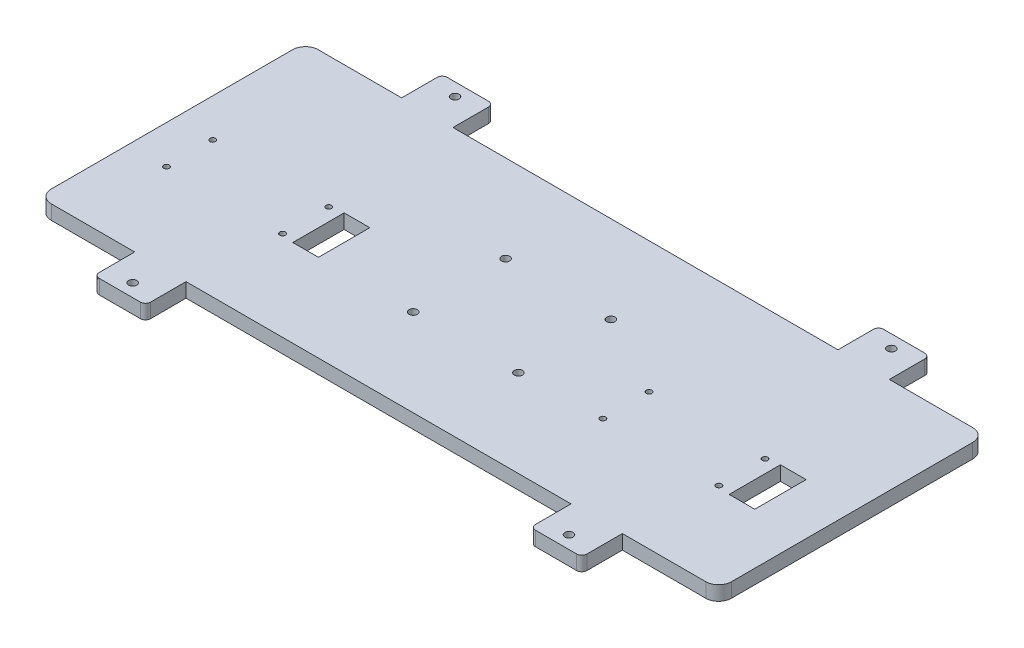
SolidWorks part; units mm, degrees
material "t5ハニカムプラダン"
ref_plane "正面" through (0, 0, 0) normal (0, 0, 1) x (1, 0, 0)
ref_plane "平面" through (0, 0, 0) normal (0, 1, 0) x (1, 0, 0)
ref_plane "右側面" through (0, 0, 0) normal (1, 0, 0) x (0, 0, -1)
sketch "ｽｹｯﾁ1" plane through (0, 0, 0) normal (0, 1, 0) x (1, 0, 0)
  line L1 (-132.5, 52) -> (132.5, 52)
  line L2 (-132.5, 52) -> (-132.5, -52)
  line L3 (-132.5, -52) -> (132.5, -52)
  line L4 (132.5, 52) -> (132.5, -52)
  line L5 (-132.5, 52) -> (132.5, -52) construction
  line L6 (-132.5, -52) -> (132.5, 52) construction
  point P0 (0, 0)
  dimension "D1" = 265
  dimension "D2" = 104
extrude "ﾎﾞｽ - 押し出し1" add sketch "ｽｹｯﾁ1" along normal blind 5.6
sketch "ｽｹｯﾁ2" plane through (0, 0, 0) normal (0, 1, 0) x (1, 0, 0)
  line L0 (0, 52) -> (0, 0) construction
  line L1 (132.5, 52) -> (-132.5, 52) construction
  line L2 (0, 0) -> (20.5, 0) construction
  line L3 (-20.5, 18) -> (20.5, 18) construction
  line L4 (-20.5, 18) -> (-20.5, -18) construction
  line L5 (-20.5, -18) -> (20.5, -18) construction
  line L6 (20.5, 18) -> (20.5, -18) construction
  line L7 (-20.5, 18) -> (20.5, -18) construction
  line L8 (-20.5, -18) -> (20.5, 18) construction
  circle A0 centre (20.5, 18) radius 1.6
  circle A1 centre (20.5, -18) radius 1.6
  circle A2 centre (-20.5, -18) radius 1.6
  circle A3 centre (-20.5, 18) radius 1.6
  dimension "D4" = 3.2
  dimension "D1" = 41
  dimension "D2" = 36
  dimension "D3" = 52
extrude "ｶｯﾄ - 押し出し4" cut sketch "ｽｹｯﾁ2" along normal through all
sketch "ｽｹｯﾁ4" plane through (0, 5.6, 0) normal (0, 1, 0) x (1, 0, 0)
  line L0 (0, 0) -> (0, 52) construction
  line L1 (132.5, 52) -> (-132.5, 52) construction
  line L2 (75, 1) -> (75, -8) construction
  line L3 (52.4, 1) -> (97.6, 1) construction
  line L4 (52.4, 1) -> (52.4, -17) construction
  line L5 (52.4, -17) -> (97.6, -17) construction
  line L6 (97.6, 1) -> (97.6, -17) construction
  line L7 (52.4, 1) -> (97.6, -17) construction
  line L8 (52.4, -17) -> (97.6, 1) construction
  line L9 (75, -8) -> (97.6, -8) construction
  line L10 (97.6, -8) -> (107.6, -8) construction
  line L11 (-67.4, 2) -> (-57.4, 2)
  line L16 (102.6, 2) -> (112.6, 2)
  line L17 (102.6, 2) -> (102.6, -18)
  line L18 (102.6, -18) -> (112.6, -18)
  line L19 (112.6, 2) -> (112.6, -18)
  line L20 (-67.4, 2) -> (-67.4, -18)
  line L21 (-67.4, -18) -> (-57.4, -18)
  line L22 (-57.4, 2) -> (-57.4, -18)
  line L23 (-95, 1) -> (-95, -8) construction
  line L24 (-117.6, 1) -> (-72.4, 1) construction
  line L25 (-117.6, 1) -> (-117.6, -17) construction
  line L26 (-117.6, -17) -> (-72.4, -17) construction
  line L27 (-72.4, 1) -> (-72.4, -17) construction
  line L32 (102.6, 2) -> (112.6, -18) construction
  line L33 (102.6, -18) -> (112.6, 2) construction
  line L34 (-117.6, 1) -> (-72.4, -17) construction
  line L39 (-117.6, -17) -> (-72.4, 1) construction
  line L40 (-95, -8) -> (-72.4, -8) construction
  line L41 (-72.4, -8) -> (-62.4, -8) construction
  line L42 (-67.4, 2) -> (-57.4, -18) construction
  line L43 (-67.4, -18) -> (-57.4, 2) construction
  line L44 (75, -8) -> (-95, -8) construction
  circle A0 centre (97.6, 1) radius 1.1
  circle A1 centre (97.6, -17) radius 1.1
  circle A2 centre (52.4, 1) radius 1.1
  circle A3 centre (52.4, -17) radius 1.1
  circle A8 centre (-72.4, 1) radius 1.1
  circle A9 centre (-72.4, -17) radius 1.1
  circle A10 centre (-117.6, 1) radius 1.1
  circle A11 centre (-117.6, -17) radius 1.1
  point P5 (75, -8)
  point P23 (-95, -8)
  dimension "D3" = 2.2
  dimension "D1" = 45.2
  dimension "D2" = 18
  dimension "D4" = 60
  dimension "D5" = 10
  dimension "D6" = 20
  dimension "D7" = 10
  dimension "D8" = 75
  dimension "D10" = 170
  dimension "D9" = 2
extrude "ｶｯﾄ - 押し出し6" cut sketch "ｽｹｯﾁ4" against normal through all
sketch "ｽｹｯﾁ5" plane through (0, 5.6, 0) normal (0, 1, 0) x (1, 0, 0)
  line L0 (132.5, 52) -> (-132.5, 52) construction
  line L1 (75, 67.8) -> (95, 67.8)
  line L2 (75, 67.8) -> (75, 52)
  line L3 (75, 52) -> (95, 52)
  line L4 (95, 67.8) -> (95, 52)
  line L5 (0, 52) -> (0, 0) construction
  line L6 (0, 0) -> (132.5, 0) construction
  line L7 (132.5, -52) -> (132.5, 52) construction
  line L8 (85, 67.8) -> (85, 62.8) construction
  line L9 (-85, 67.8) -> (-85, 62.8) construction
  line L10 (-95, 67.8) -> (-95, 52)
  line L11 (-75, 52) -> (-95, 52)
  line L12 (-75, 67.8) -> (-75, 52)
  line L13 (-75, 67.8) -> (-95, 67.8)
  line L14 (85, -67.8) -> (85, -62.8) construction
  line L15 (95, -67.8) -> (95, -52)
  line L16 (75, -52) -> (95, -52)
  line L17 (75, -67.8) -> (75, -52)
  line L18 (75, -67.8) -> (95, -67.8)
  line L19 (-85, -67.8) -> (-85, -62.8) construction
  line L20 (-75, -67.8) -> (-95, -67.8)
  line L21 (-75, -67.8) -> (-75, -52)
  line L22 (-75, -52) -> (-95, -52)
  line L23 (-95, -67.8) -> (-95, -52)
  circle A0 centre (85, 62.8) radius 1.6
  circle A1 centre (-85, 62.8) radius 1.6
  circle A2 centre (85, -62.8) radius 1.6
  circle A3 centre (-85, -62.8) radius 1.6
  dimension "D3" = 3.2
  dimension "D1" = 20
  dimension "D2" = 15.8
  dimension "D4" = 5
  dimension "D5" = 150
extrude "ﾎﾞｽ - 押し出し2" add sketch "ｽｹｯﾁ5" against normal blind 5.6
fillet "ﾌｨﾚｯﾄ1" radius 5 4 edges at (-132.5, 2.8, -52) (132.5, 2.8, -52) (132.5, 2.8, 52) (-132.5, 2.8, 52)
fillet "ﾌｨﾚｯﾄ2" radius 2 8 edges at (-95, 2.8, -67.8) (-75, 2.8, -67.8) (75, 2.8, -67.8) (95, 2.8, -67.8) (75, 2.8, 67.8) (95, 2.8, 67.8) (-75, 2.8, 67.8) (-95, 2.8, 67.8)
